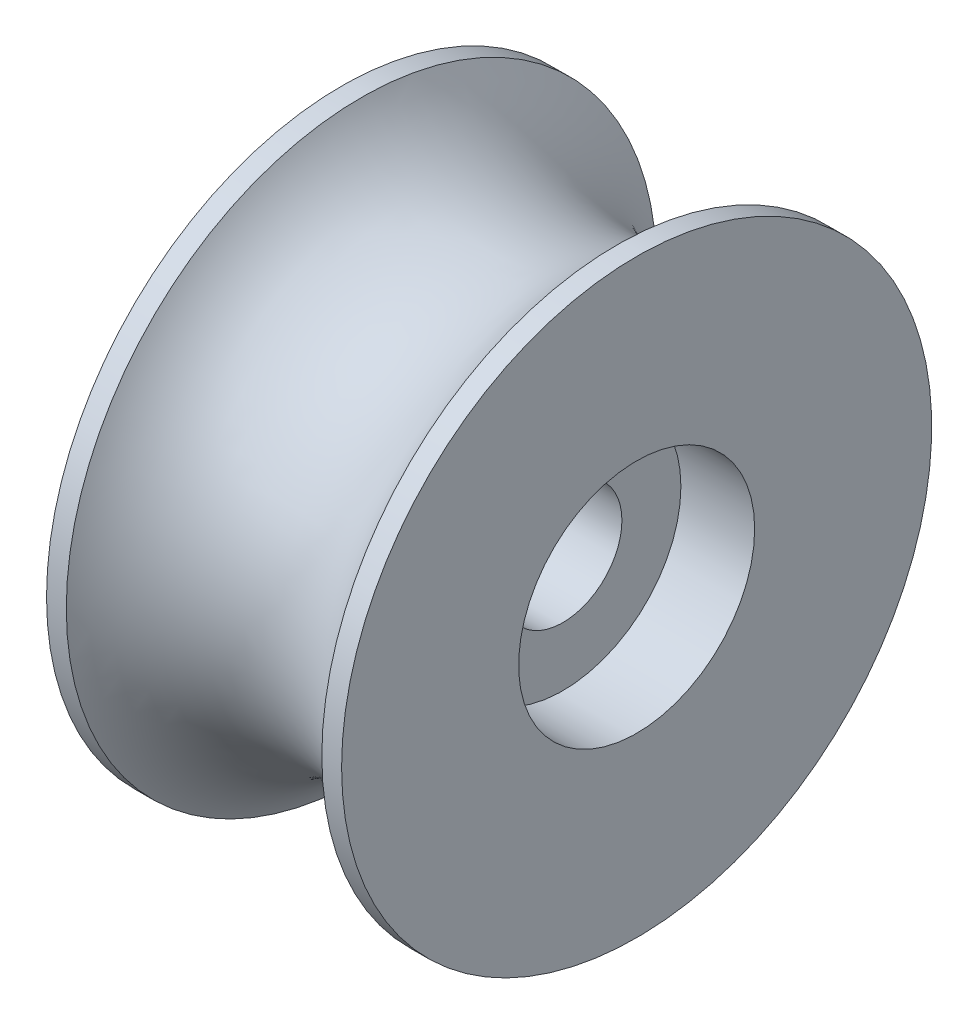
SolidWorks part; units mm, degrees
ref_plane "前视基准面" through (0, 0, 0) normal (0, 0, 1) x (1, 0, 0)
ref_plane "上视基准面" through (0, 0, 0) normal (0, 1, 0) x (1, 0, 0)
ref_plane "右视基准面" through (0, 0, 0) normal (1, 0, 0) x (0, 0, -1)
sketch "草图1" plane through (0, 0, 0) normal (0, 1, 0) x (1, 0, 0)
  line L0 (0, 15) -> (0, -10) construction
  line L1 (-10, 10) -> (10, 10) construction
  line L2 (-10, 10) -> (-10, -10)
  line L3 (-10, -10) -> (10, -10)
  line L4 (10, 10) -> (10, -10)
  line L5 (-10, 10) -> (10, -10) construction
  line L6 (-10, -10) -> (10, 10) construction
  line L7 (-8.6603, 10) -> (-10, 10)
  line L8 (8.6603, 10) -> (10, 10)
  circle A0 centre (0, 15) radius 10 construction
  arc A1 (-8.6603, 10) -> (8.6603, 10) centre (0, 15) ccw
  point P0 (0, 0)
  dimension "D3" = 20
  dimension "D1" = 20
  dimension "D2" = 20
  dimension "D4" = 25
revolve "旋转1" add sketch "草图1" angle 360 about L3
sketch "草图2" plane through (10, 0, 0) normal (1, 0, 0) x (0, 0, -1)
  circle A0 centre (-10, 0) radius 4
  dimension "D1" = 8
extrude "切除-拉伸1" cut sketch "草图2" against normal blind 55
sketch "草图3" plane through (10, 0, 0) normal (1, 0, 0) x (0, 0, -1)
  circle A0 centre (-10, 0) radius 8
  dimension "D1" = 16
extrude "切除-拉伸2" cut sketch "草图3" against normal blind 5
sketch "草图4" plane through (-10, 0, 0) normal (-1, 0, 0) x (0, 0, 1)
  circle A0 centre (10, 0) radius 8
  dimension "D1" = 16
extrude "切除-拉伸3" cut sketch "草图4" against normal blind 5
